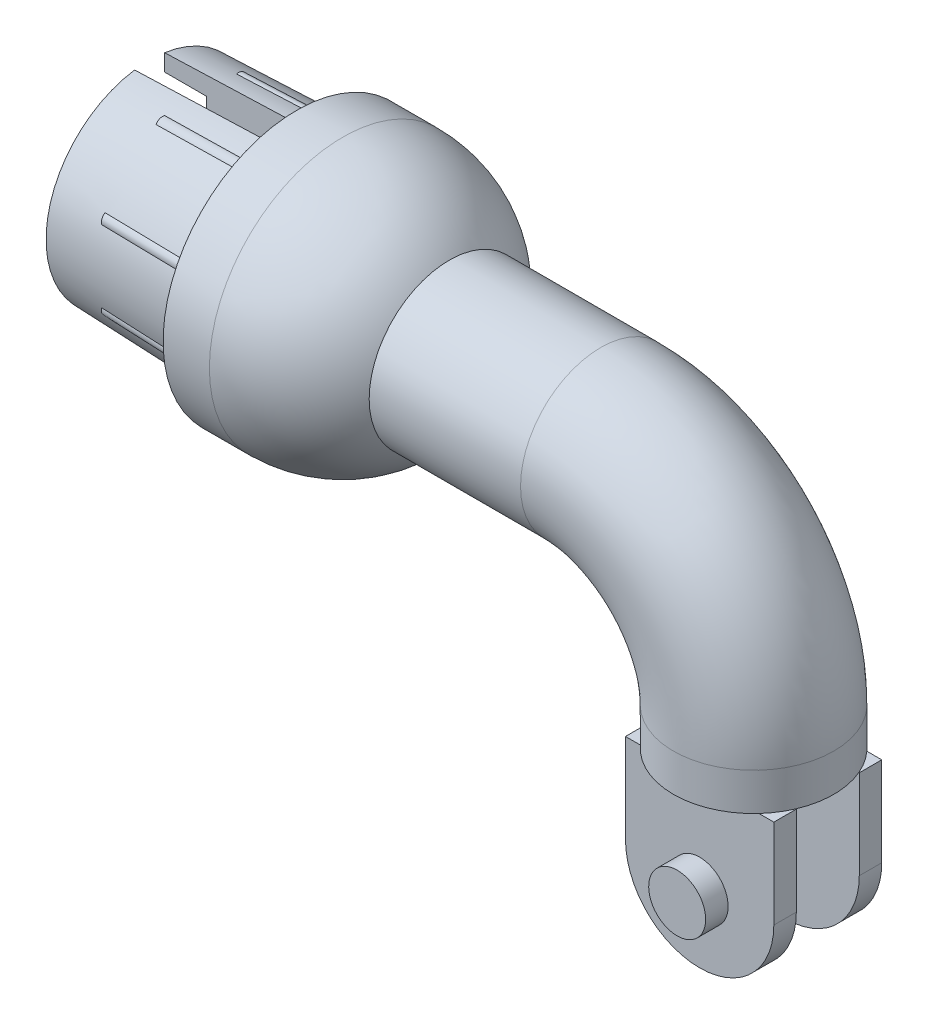
SolidWorks part; units mm, degrees
ref_plane "Front" through (0, 0, 0) normal (0, 0, 1) x (1, 0, 0)
ref_plane "Top" through (0, 0, 0) normal (0, 1, 0) x (1, 0, 0)
ref_plane "Right" through (0, 0, 0) normal (1, 0, 0) x (0, 0, -1)
ref_plane "Plane4" through (0, 6.4, 0) normal (0, 1, 0) x (-1, 0, 0)
sketch "Sketch1" plane through (0, 6.4, 0) normal (0, 1, 0) x (-1, 0, 0)
  circle A0 centre (0, 0) radius 5.35
  dimension "D1" = 10.7
sketch "Sketch2" plane through (0, 0, 0) normal (0, 0, 1) x (1, 0, 0)
  line L0 (0, 6.4) -> (0, 8.9)
  line L1 (-10.2, 19.1) -> (-25.4, 19.1)
  line L2 (50, 6.4) -> (-50, 6.4) construction
  arc A0 (-10.2, 19.1) -> (0, 8.9) centre (-10.2, 8.9) cw
  point P8 (0, 19.1)
  dimension "D3" = 10.2
  dimension "D1" = 12.7
  dimension "D2" = 25.4
sweep "Base-Sweep" add profiles "Sketch1" path "Sketch2"
sketch "Sketch3" plane through (0, 0, 0) normal (0, 0, 1) x (1, 0, 0)
  line L0 (-36.1722, 19.1) -> (-64.353, 19.1) construction
  line L1 (-10.2, 19.1) -> (-25.4, 19.1) construction
  line L2 (-27.4125, 28) -> (-30.5, 28)
  line L3 (-30.5, 28) -> (-30.5, 19.1)
  line L4 (-30.5, 19.1) -> (-18.5125, 19.1)
  line L5 (0, -50) -> (0, 50) construction
  line L6 (-10.2, 24.45) -> (-25.4, 24.45) construction
  line L7 (-10.2, 24.45) -> (-25.4, 24.45) construction
  arc A0 (-18.5125, 19.1) -> (-27.4125, 28) centre (-27.4125, 19.1) ccw
  point P13 (-20.3, 24.45)
  dimension "D3" = 8.9
  dimension "D1" = 17.8
  dimension "D2" = 30.5
  dimension "D4" = 3.0875
  dimension "D5" = 20.3
revolve "Boss-Revolve1" add sketch "Sketch3" angle 360 about L0
sketch "Sketch4" plane through (-30.5, 0, 0) normal (-1, 0, 0) x (0, 0, 1)
  circle A0 centre (0, 19.1) radius 7.25
  dimension "D1" = 14.5
extrude "Boss-Extrude1" add sketch "Sketch4" along normal blind 9.8 draft 2
shell "Shell1" thickness 2
ref_plane "Plane5" through (0, 2.7971, 6.7529) normal (0, 0.3827, 0.9239) x (1, 0, 0)
sketch "Sketch6" plane through (0, 2.7971, 6.7529) normal (0, 0.3827, 0.9239) x (1, 0, 0)
  line L0 (-36.9, 24.6726) -> (-30.5, 24.8961)
  line L1 (-30.5, 24.8961) -> (-40.3, 24.5539) construction
  dimension "D1" = 6.4
sketch "Sketch7" plane through (-30.5, 0, 0) normal (-1, 0, 0) x (0, 0, 1)
  line L0 (12.1146, -10.1472) -> (1.3912, 15.7414) construction
  line L1 (-2.6214, 25.4286) -> (-2.8588, 26.0018) construction
  circle A0 centre (-2.6214, 25.4286) radius 0.5
  circle A1 centre (0, 19.1) radius 7.25 construction
  circle A2 centre (0, 19.1) radius 7.25 construction
  dimension "D1" = 1
  dimension "D2" = 0.1
sweep "Boss-Sweep1" add profiles "Sketch7" path "Sketch6"
pattern_circular "CirPattern1" count 8 every 45 about axis through (-36.1722, 19.1, 0) along (-1, 0, 0) of "Boss-Sweep1"
sketch "Sketch8" plane through (-40.3, 0, 0) normal (-1, 0, 0) x (0, 0, 1)
  circle A0 centre (0, 19.1) radius 5.8
  dimension "D1" = 11.6
extrude "Cut-Extrude1" cut sketch "Sketch8" against normal blind 2.8
sketch "Sketch9" plane through (0, 0, 0) normal (0, 1, 0) x (1, 0, 0)
  line L1 (-31.14, 1) -> (-31.14, -1)
  line L2 (-40.3, 1) -> (-31.14, 1)
  line L3 (-40.3, 1) -> (-40.3, -1)
  line L4 (-31.14, -1) -> (-40.3, -1)
  line L5 (-50, 0) -> (50, 0) construction
  line L6 (-40.3, 6.9078) -> (-40.3, -6.9078) construction
  line L7 (-30.5, 8.9) -> (-30.5, -8.9) construction
  point P5 (-40.3, 0)
  dimension "D1" = 2
  dimension "D2" = 0.64
extrude "Cut-Extrude2" cut sketch "Sketch9" along normal through all
ref_plane "Plane6" through (0, 0, -3.6) normal (0, 0, 1) x (1, 0, 0)
sketch "Sketch10" plane through (0, 12.319, -3.6) normal (0, 0, -1) x (1, 0, 0)
  line L0 (-4.95, 5.919) -> (4.95, 5.919)
  line L1 (-4.95, 5.919) -> (-4.95, 11.869)
  line L3 (4.95, 11.869) -> (4.95, 5.919)
  line L4 (0, -37.681) -> (0, 62.319) construction
  line L5 (5.35, 5.919) -> (-5.35, 5.919) construction
  arc A0 (-4.95, 11.869) -> (4.95, 11.869) centre (0, 11.869) cw
  dimension "D1" = 9.9
  dimension "D2" = 10.9
extrude "Boss-Extrude2" add sketch "Sketch10" against normal blind 1.5
sketch "Sketch11" plane through (0, 0, -3.6) normal (0, 0, -1) x (-1, 0, 0)
  circle A0 centre (0, 0) radius 1.9
  dimension "D1" = 3.8
extrude "Boss-Extrude3" add sketch "Sketch11" along normal blind 1.5
mirror "Mirror1" about plane through (0, 0, 0) normal (0, 0, 1) of "Boss-Extrude3", "Boss-Extrude2"
